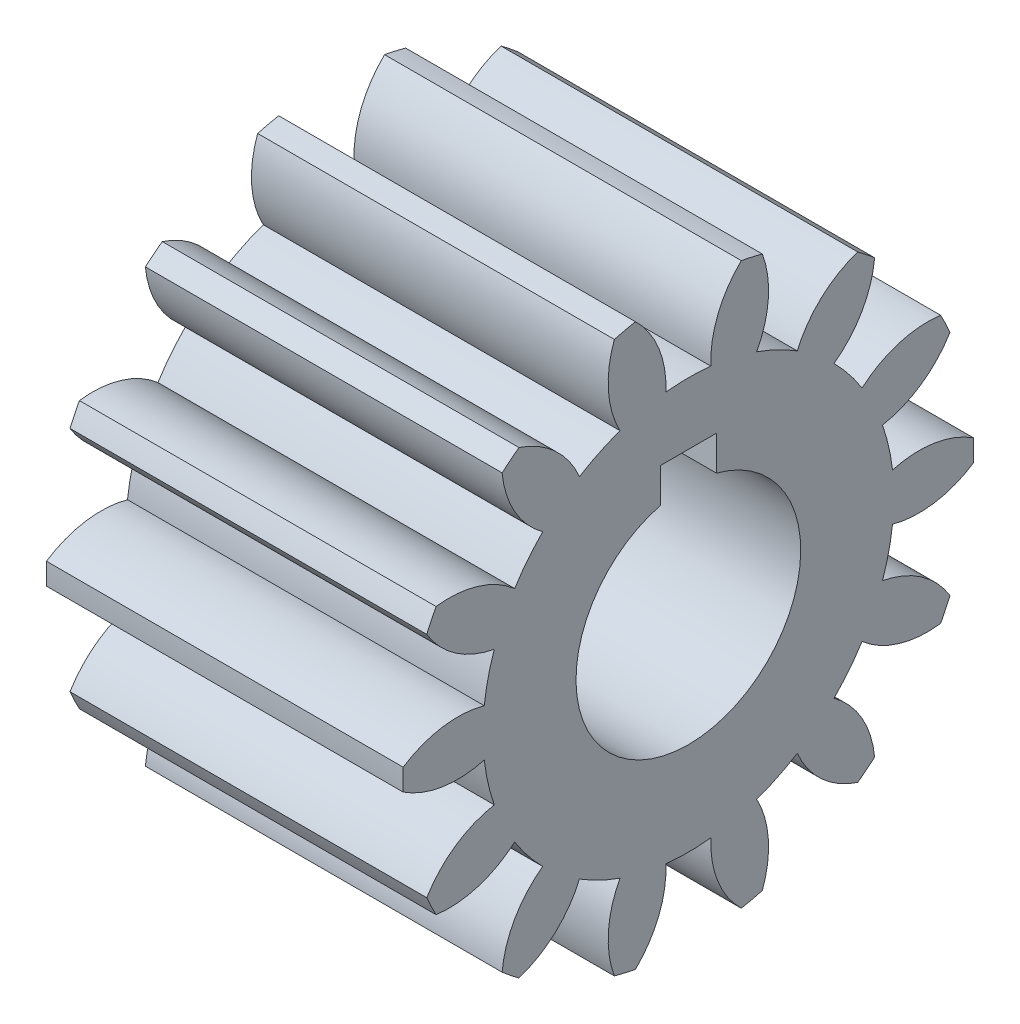
SolidWorks part; units mm, degrees
material "Cast Alloy Steel"
ref_plane "Front Plane" through (0, 0, 0) normal (0, 0, 1) x (1, 0, 0)
ref_plane "Top Plane" through (0, 0, 0) normal (0, 1, 0) x (1, 0, 0)
ref_plane "Right Plane" through (0, 0, 0) normal (1, 0, 0) x (0, 0, -1)
ref_plane "Plane1" through (0, 0, 0) normal (-1, 0, 0) x (0, -1, 0)
sketch "Sketch1" plane through (0, 0, 0) normal (-1, 0, 0) x (0, -1, 0)
  line L0 (-5.1054, 1) -> (-3.873, 1)
  line L1 (-3.873, -1) -> (-5.1054, -1)
  line L2 (-5.1054, -1) -> (-5.1054, 1)
  arc A0 (-8.1774, -6.0295) -> (-7.698, -6.6307) centre (0, 0) ccw
  arc A1 (-7.698, -6.6307) -> (-5.1596, -5.1856) centre (-8.0328, -3.0905) ccw
  arc A2 (-5.1596, -5.1856) -> (-3.9075, -6.1841) centre (0, 0) ccw
  arc A3 (-3.9075, -6.1841) -> (-4.7515, -8.9805) centre (-1.2256, -8.5191) ccw
  arc A4 (-4.7515, -8.9805) -> (-4.0587, -9.3141) centre (0, 0) ccw
  arc A5 (-4.0587, -9.3141) -> (-2.3986, -6.9108) centre (-5.8964, -6.2698) ccw
  arc A6 (-2.3986, -6.9108) -> (-0.8374, -7.2671) centre (0, 0) ccw
  arc A7 (-0.8374, -7.2671) -> (-0.3845, -10.1527) centre (2.5921, -8.2072) ccw
  arc A8 (-0.3845, -10.1527) -> (0.3845, -10.1527) centre (0, 0) ccw
  arc A9 (0.3845, -10.1527) -> (0.8374, -7.2671) centre (-2.5921, -8.2072) ccw
  arc A10 (0.8374, -7.2671) -> (2.3986, -6.9108) centre (0, 0) ccw
  arc A11 (2.3986, -6.9108) -> (4.0587, -9.3141) centre (5.8964, -6.2698) ccw
  arc A12 (4.0587, -9.3141) -> (4.7515, -8.9805) centre (0, 0) ccw
  arc A13 (4.7515, -8.9805) -> (3.9075, -6.1841) centre (1.2256, -8.5191) ccw
  arc A14 (3.9075, -6.1841) -> (5.1596, -5.1856) centre (0, 0) ccw
  arc A15 (5.1596, -5.1856) -> (7.698, -6.6307) centre (8.0328, -3.0905) ccw
  arc A16 (7.698, -6.6307) -> (8.1774, -6.0295) centre (0, 0) ccw
  arc A17 (8.1774, -6.0295) -> (6.2037, -3.8763) centre (4.8005, -7.1437) ccw
  arc A18 (6.2037, -3.8763) -> (6.8986, -2.4335) centre (0, 0) ccw
  arc A19 (6.8986, -2.4335) -> (9.8126, -2.634) centre (8.5783, 0.7008) ccw
  arc A20 (9.8126, -2.634) -> (9.9837, -1.8843) centre (0, 0) ccw
  arc A21 (9.9837, -1.8843) -> (7.2712, -0.8007) centre (7.4246, -4.3534) ccw
  arc A22 (7.2712, -0.8007) -> (7.2712, 0.8007) centre (0, 0) ccw
  arc A23 (7.2712, 0.8007) -> (9.9837, 1.8843) centre (7.4246, 4.3534) ccw
  arc A24 (9.9837, 1.8843) -> (9.8126, 2.634) centre (0, 0) ccw
  arc A25 (9.8126, 2.634) -> (6.8986, 2.4335) centre (8.5783, -0.7008) ccw
  arc A26 (6.8986, 2.4335) -> (6.2037, 3.8763) centre (0, 0) ccw
  arc A27 (6.2037, 3.8763) -> (8.1774, 6.0295) centre (4.8005, 7.1437) ccw
  arc A28 (8.1774, 6.0295) -> (7.698, 6.6307) centre (0, 0) ccw
  arc A29 (7.698, 6.6307) -> (5.1596, 5.1856) centre (8.0328, 3.0905) ccw
  arc A30 (5.1596, 5.1856) -> (3.9075, 6.1841) centre (0, 0) ccw
  arc A31 (3.9075, 6.1841) -> (4.7515, 8.9805) centre (1.2256, 8.5191) ccw
  arc A32 (4.7515, 8.9805) -> (4.0587, 9.3141) centre (0, 0) ccw
  arc A33 (4.0587, 9.3141) -> (2.3986, 6.9108) centre (5.8964, 6.2698) ccw
  arc A34 (2.3986, 6.9108) -> (0.8374, 7.2671) centre (0, 0) ccw
  arc A35 (0.8374, 7.2671) -> (0.3845, 10.1527) centre (-2.5921, 8.2072) ccw
  arc A36 (0.3845, 10.1527) -> (-0.3845, 10.1527) centre (0, 0) ccw
  arc A37 (-0.3845, 10.1527) -> (-0.8374, 7.2671) centre (2.5921, 8.2072) ccw
  arc A38 (-0.8374, 7.2671) -> (-2.3986, 6.9108) centre (0, 0) ccw
  arc A39 (-2.3986, 6.9108) -> (-4.0587, 9.3141) centre (-5.8964, 6.2698) ccw
  arc A40 (-4.0587, 9.3141) -> (-4.7515, 8.9805) centre (0, 0) ccw
  arc A41 (-4.7515, 8.9805) -> (-3.9075, 6.1841) centre (-1.2256, 8.5191) ccw
  arc A42 (-3.9075, 6.1841) -> (-5.1596, 5.1856) centre (0, 0) ccw
  arc A43 (-5.1596, 5.1856) -> (-7.698, 6.6307) centre (-8.0328, 3.0905) ccw
  arc A44 (-7.698, 6.6307) -> (-8.1774, 6.0295) centre (0, 0) ccw
  arc A45 (-8.1774, 6.0295) -> (-6.2037, 3.8763) centre (-4.8005, 7.1437) ccw
  arc A46 (-6.2037, 3.8763) -> (-6.8986, 2.4335) centre (0, 0) ccw
  arc A47 (-6.8986, 2.4335) -> (-9.8126, 2.634) centre (-8.5783, -0.7008) ccw
  arc A48 (-9.8126, 2.634) -> (-9.9837, 1.8843) centre (0, 0) ccw
  arc A49 (-9.9837, 1.8843) -> (-7.2712, 0.8007) centre (-7.4246, 4.3534) ccw
  arc A50 (-7.2712, 0.8007) -> (-7.2712, -0.8007) centre (0, 0) ccw
  arc A51 (-7.2712, -0.8007) -> (-9.9837, -1.8843) centre (-7.4246, -4.3534) ccw
  arc A52 (-9.9837, -1.8843) -> (-9.8126, -2.634) centre (0, 0) ccw
  arc A53 (-9.8126, -2.634) -> (-6.8986, -2.4335) centre (-8.5783, 0.7008) ccw
  arc A54 (-6.8986, -2.4335) -> (-6.2037, -3.8763) centre (0, 0) ccw
  arc A55 (-6.2037, -3.8763) -> (-8.1774, -6.0295) centre (-4.8005, -7.1437) ccw
  arc A56 (-3.873, 1) -> (-3.873, -1) centre (0, 0) cw
extrude "Boss-Extrude1" add sketch "Sketch1" against normal blind 12.7
